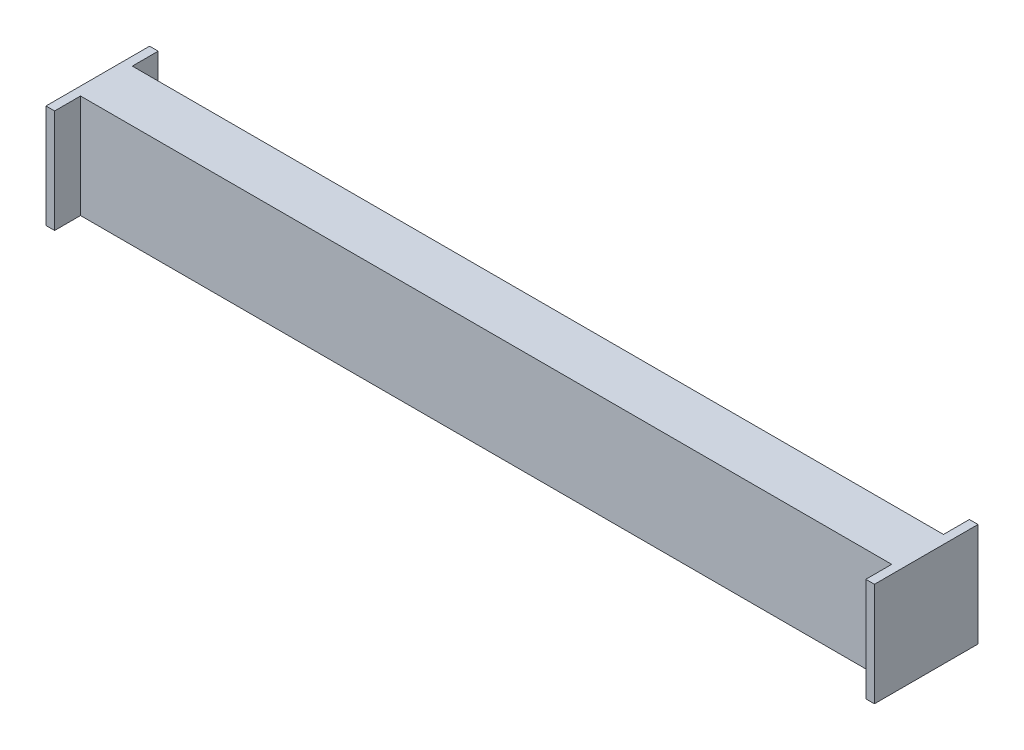
SolidWorks part; units mm, degrees
ref_plane "Front Plane" through (0, 0, 0) normal (0, 0, 1) x (1, 0, 0)
ref_plane "Top Plane" through (0, 0, 0) normal (0, 1, 0) x (1, 0, 0)
ref_plane "Right Plane" through (0, 0, 0) normal (1, 0, 0) x (0, 0, -1)
sketch "Sketch1" plane through (0, 0, 0) normal (1, 0, 0) x (0, 0, -1)
  line L1 (-38.1, -76.2) -> (38.1, -76.2)
  line L2 (-38.1, -76.2) -> (-38.1, 76.2)
  line L3 (-38.1, 76.2) -> (38.1, 76.2)
  line L4 (38.1, -76.2) -> (38.1, 76.2)
  line L5 (-38.1, -76.2) -> (38.1, 76.2) construction
  line L6 (-38.1, 76.2) -> (38.1, -76.2) construction
  point P0 (0, 0)
  dimension "D1" = 76.2
  dimension "D2" = 152.4
extrude "Boss-Extrude1" add sketch "Sketch1" along normal blind 1219.2
sketch "Sketch2" plane through (1219.2, 0, 0) normal (1, 0, 0) x (0, 0, -1)
  line L1 (-76.2, -76.2) -> (76.2, -76.2)
  line L2 (-76.2, -76.2) -> (-76.2, 76.2)
  line L3 (-76.2, 76.2) -> (76.2, 76.2)
  line L4 (76.2, -76.2) -> (76.2, 76.2)
  line L5 (-76.2, -76.2) -> (76.2, 76.2) construction
  line L6 (-76.2, 76.2) -> (76.2, -76.2) construction
  point P0 (0, 0)
  dimension "D1" = 152.4
  dimension "D2" = 152.4
extrude "Boss-Extrude2" add sketch "Sketch2" against normal blind 12.7
sketch "Sketch3" plane through (0, 0, 0) normal (-1, 0, 0) x (0, 0, 1)
  line L1 (-76.2, -76.2) -> (76.2, -76.2)
  line L2 (-76.2, -76.2) -> (-76.2, 76.2)
  line L3 (-76.2, 76.2) -> (76.2, 76.2)
  line L4 (76.2, -76.2) -> (76.2, 76.2)
  line L5 (-76.2, -76.2) -> (76.2, 76.2) construction
  line L6 (-76.2, 76.2) -> (76.2, -76.2) construction
  point P0 (0, 0)
  dimension "D1" = 152.4
  dimension "D2" = 152.4
extrude "Boss-Extrude3" add sketch "Sketch3" against normal blind 12.7
